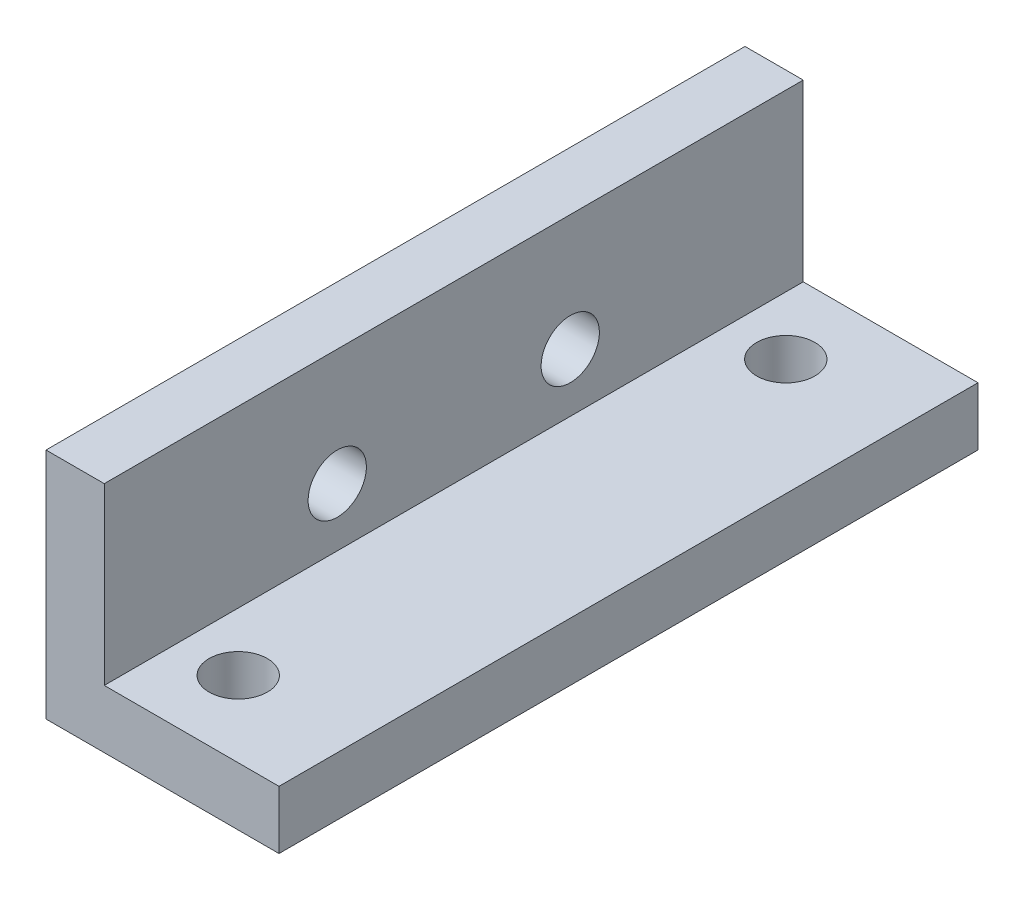
SolidWorks part; units mm, degrees
material "6063-T5"
ref_plane "Front Plane" through (0, 0, 0) normal (0, 0, 1) x (1, 0, 0)
ref_plane "Top Plane" through (0, 0, 0) normal (0, 1, 0) x (1, 0, 0)
ref_plane "Right Plane" through (0, 0, 0) normal (1, 0, 0) x (0, 0, -1)
sketch "Sketch1" plane through (0, 0, 0) normal (0, 0, 1) x (1, 0, 0)
  line L0 (0, 12.7) -> (0, 0)
  line L1 (0, 0) -> (12.7, 0)
  line L2 (0, 12.7) -> (3.175, 12.7)
  line L3 (3.175, 12.7) -> (3.175, 3.175)
  line L4 (3.175, 3.175) -> (12.7, 3.175)
  line L5 (12.7, 3.175) -> (12.7, 0)
  dimension "D1" = 12.7
  dimension "D2" = 12.7
  dimension "D3" = 3.175
  dimension "D4" = 3.175
extrude "Boss-Extrude1" add sketch "Sketch1" along normal blind 38.1
sketch "Sketch2" plane through (0, 0, 0) normal (-1, 0, 0) x (0, 0, 1)
  line L0 (19.05, 12.7) -> (19.05, 0) construction
  line L1 (38.1, 12.7) -> (0, 12.7) construction
  line L2 (38.1, 0) -> (0, 0) construction
  circle A0 centre (12.7, 6.35) radius 1.5875
  circle A1 centre (25.4, 6.35) radius 1.5875
  dimension "D1" = 3.175
  dimension "D2" = 6.35
  dimension "D3" = 6.35
extrude "Cut-Extrude1" cut sketch "Sketch2" against normal through all
sketch "Sketch3" plane through (0, 0, 0) normal (0, -1, 0) x (1, 0, 0)
  line L0 (0, 19.05) -> (12.7, 19.05) construction
  line L1 (0, 38.1) -> (0, 0) construction
  line L2 (12.7, 38.1) -> (12.7, 0) construction
  circle A0 centre (6.35, 4.1275) radius 1.5875
  circle A1 centre (6.35, 33.9725) radius 1.5875
  dimension "D1" = 3.175
  dimension "D2" = 6.35
  dimension "D3" = 14.9225
extrude "Cut-Extrude2" cut sketch "Sketch3" against normal through all
